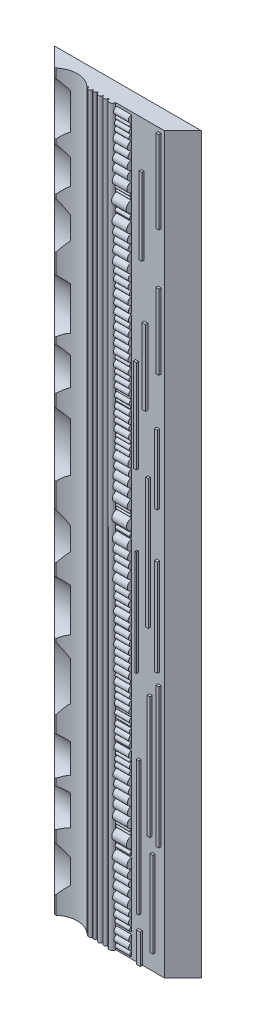
SolidWorks part; units mm, degrees
ref_plane "前视基准面" through (0, 0, 0) normal (0, 0, 1) x (1, 0, 0)
ref_plane "上视基准面" through (0, 0, 0) normal (0, 1, 0) x (1, 0, 0)
ref_plane "右视基准面" through (0, 0, 0) normal (1, 0, 0) x (0, 0, -1)
sketch "草图1" plane through (0, 0, 0) normal (0, 0, 1) x (1, 0, 0)
  line L1 (0, 0) -> (50, 0)
  line L2 (0, 0) -> (0, 10)
  line L3 (0, 10) -> (50, 10)
  line L4 (50, 0) -> (50, 10)
sketch "草图2" plane through (0, 0, 0) normal (1, 0, 0) x (0, 0, -1)
  line L0 (0, 10) -> (-1.257, 8.743)
  line L2 (0, 0) -> (0, 10)
  line L4 (-1.257, 1.257) -> (-1.257, 8.743)
  line L5 (0, 0) -> (-1.257, 1.257)
extrude "凸台-拉伸1" add sketch "草图2" along normal blind 50
sketch "草图4" plane through (0, 0, 0) normal (0, 1, 0) x (1, 0, 0)
  line L0 (0.6235, -1.257) -> (4.1918, -1.257)
  line L1 (45.7548, -1.257) -> (48.7813, -1.257)
  line L2 (42.3754, -1.257) -> (44.9543, -1.257)
  line L3 (39.288, -1.257) -> (41.9161, -1.257)
  line L4 (33.8809, -1.257) -> (38.1709, -1.257)
  line L5 (30.0238, -1.257) -> (33.6686, -1.257)
  line L6 (20.0613, -1.257) -> (24.3897, -1.257)
  line L7 (12.228, -1.257) -> (15.8643, -1.257)
  line L8 (7.7148, -1.257) -> (10.8649, -1.257)
  line L9 (4.5051, -1.257) -> (7.4446, -1.257)
  line L10 (16.3112, -1.257) -> (19.2037, -1.257)
  line L11 (26.0537, -1.257) -> (29.207, -1.257)
  arc A0 (4.1918, -1.257) -> (0.6235, -1.257) centre (2.4077, -3.4751) ccw
  arc A1 (7.4446, -1.257) -> (4.5051, -1.257) centre (5.9749, -3.1147) ccw
  arc A4 (15.8643, -1.257) -> (12.228, -1.257) centre (14.0461, -2.7544) ccw
  arc A6 (24.3897, -1.257) -> (20.0613, -1.257) centre (22.2255, -3.7994) ccw
  arc A10 (41.9161, -1.257) -> (39.288, -1.257) centre (40.6021, -2.1419) ccw
  arc A11 (44.9543, -1.257) -> (42.3754, -1.257) centre (43.6648, -1.9257) ccw
  arc A12 (48.7813, -1.257) -> (45.7548, -1.257) centre (47.2681, -3.3782) ccw
  arc A13 (10.8649, -1.257) -> (7.7148, -1.257) centre (9.2898, -3.7994) ccw
  arc A14 (19.2037, -1.257) -> (16.3112, -1.257) centre (17.7575, -2.7544) ccw
  arc A15 (29.207, -1.257) -> (26.0537, -1.257) centre (27.6304, -3.7994) ccw
  arc A16 (33.6686, -1.257) -> (30.0238, -1.257) centre (31.8462, -2.7544) ccw
  arc A17 (38.1709, -1.257) -> (33.8809, -1.257) centre (36.0259, -5.1131) ccw
extrude "切除-拉伸1" cut sketch "草图4" along normal blind 2
sketch "草图5" plane through (0, 0, 0) normal (-1, 0, 0) x (0, 0, 1)
  circle A0 centre (2.4471, 2.398) radius 1.5913
extrude "切除-拉伸2" cut sketch "草图5" against normal blind 50
sketch "草图6" plane through (0, 0, 0) normal (-1, 0, 0) x (0, 0, 1)
  line L0 (1.257, 8.743) -> (1.257, 3.4545) construction
  circle A0 centre (1.257, 3.7317) radius 0.155
  circle A1 centre (1.257, 4.0208) radius 0.1212
  circle A2 centre (1.257, 4.4031) radius 0.1679
  circle A3 centre (1.257, 4.7668) radius 0.1585
  circle A4 centre (1.257, 5.2052) radius 0.2145
extrude "凸台-拉伸2" add sketch "草图6" against normal blind 50
ref_plane "基准面1" through (0, 5.5, 0) normal (0, 1, 0) x (1, 0, 0)
sketch "草图7" plane through (0, 5.5, 0) normal (0, 1, 0) x (1, 0, 0)
  line L0 (0, -1.257) -> (50, -1.257) construction
  line L1 (50, -1.257) -> (0, -1.257) construction
  line L2 (50, -1.257) -> (0, -1.257) construction
  line L3 (0, -1.257) -> (50, -1.257) construction
  circle A0 centre (0.4046, -1.257) radius 0.2266
  circle A2 centre (1.4918, -1.257) radius 0.1784
  circle A3 centre (1.9842, -1.257) radius 0.2787
  circle A5 centre (3.1418, -1.257) radius 0.2991
  circle A6 centre (3.7531, -1.257) radius 0.2977
  circle A7 centre (4.4332, -1.257) radius 0.3186
  circle A9 centre (5.5815, -1.257) radius 0.3658
  circle A11 centre (6.8227, -1.257) radius 0.3345
  circle A12 centre (7.4693, -1.257) radius 0.2913
  circle A13 centre (8.0156, -1.257) radius 0.2335
  circle A14 centre (8.56, -1.257) radius 0.2885
  circle A15 centre (9.2122, -1.257) radius 0.3087
  circle A16 centre (9.7882, -1.257) radius 0.2281
  circle A17 centre (10.275, -1.257) radius 0.2342
  circle A19 centre (11.1651, -1.257) radius 0.2558
  circle A20 centre (11.6798, -1.257) radius 0.2208
  circle A21 centre (12.2242, -1.257) radius 0.2248
  circle A22 centre (12.6515, -1.257) radius 0.1789
  circle A23 centre (13.0956, -1.257) radius 0.2431
  circle A24 centre (13.5769, -1.257) radius 0.2235
  circle A25 centre (14.06, -1.257) radius 0.2323
  circle A26 centre (14.5449, -1.257) radius 0.2426
  circle A27 centre (14.9389, -1.257) radius 0.1416
  circle A28 centre (15.3291, -1.257) radius 0.2354
  circle A29 centre (15.7639, -1.257) radius 0.1707
  circle A30 centre (16.1708, -1.257) radius 0.193
  circle A33 centre (17.1713, -1.257) radius 0.1734
  circle A35 centre (17.8158, -1.2454) radius 0.1867
  circle A36 centre (18.2231, -1.257) radius 0.215
  circle A37 centre (18.6402, -1.257) radius 0.1872
  circle A38 centre (0.798, -1.257) radius 0.1224
  circle A39 centre (1.1234, -1.257) radius 0.1732
  circle A40 centre (2.5672, -1.257) radius 0.2444
  circle A41 centre (4.8855, -1.257) radius 0.1209
  circle A42 centre (5.1143, -1.257) radius 0.0868
  circle A43 centre (6.0345, -1.257) radius 0.0609
  circle A44 centre (6.248, -1.257) radius 0.1326
  circle A45 centre (10.7118, -1.257) radius 0.155
  circle A46 centre (16.6041, -1.257) radius 0.198
  circle A47 centre (16.9041, -1.257) radius 0.0631
  circle A48 centre (17.4633, -1.257) radius 0.0861
  circle A49 centre (19.1512, -1.2381) radius 0.2266
  circle A50 centre (20.2383, -1.2381) radius 0.1784
  circle A51 centre (20.7307, -1.2381) radius 0.2787
  circle A52 centre (21.8883, -1.2381) radius 0.2991
  circle A53 centre (22.4996, -1.2381) radius 0.2977
  circle A54 centre (23.1797, -1.2381) radius 0.3186
  circle A55 centre (24.328, -1.2381) radius 0.3658
  circle A56 centre (25.5692, -1.2381) radius 0.3345
  circle A57 centre (26.2158, -1.2381) radius 0.2913
  circle A58 centre (26.7621, -1.2381) radius 0.2335
  circle A59 centre (27.3065, -1.2381) radius 0.2885
  circle A60 centre (27.9587, -1.2381) radius 0.3087
  circle A61 centre (28.5347, -1.2381) radius 0.2281
  circle A62 centre (29.0216, -1.2381) radius 0.2342
  circle A63 centre (29.9116, -1.2381) radius 0.2558
  circle A64 centre (30.4263, -1.2381) radius 0.2208
  circle A65 centre (30.9707, -1.2381) radius 0.2248
  circle A66 centre (31.3981, -1.2381) radius 0.1789
  circle A67 centre (31.8422, -1.2381) radius 0.2431
  circle A68 centre (32.3234, -1.2381) radius 0.2235
  circle A69 centre (32.8065, -1.2381) radius 0.2323
  circle A70 centre (33.2915, -1.2381) radius 0.2426
  circle A71 centre (33.6854, -1.2381) radius 0.1416
  circle A72 centre (34.0756, -1.2381) radius 0.2354
  circle A73 centre (34.5104, -1.2381) radius 0.1707
  circle A74 centre (34.9173, -1.2381) radius 0.193
  circle A75 centre (35.9179, -1.2381) radius 0.1734
  circle A76 centre (36.5624, -1.2265) radius 0.1867
  circle A77 centre (36.9696, -1.2381) radius 0.215
  circle A78 centre (37.3868, -1.2381) radius 0.1872
  circle A79 centre (19.5445, -1.2381) radius 0.1224
  circle A80 centre (19.8699, -1.2381) radius 0.1732
  circle A81 centre (21.3138, -1.2381) radius 0.2444
  circle A82 centre (23.6321, -1.2381) radius 0.1209
  circle A83 centre (23.8608, -1.2381) radius 0.0868
  circle A84 centre (24.7811, -1.2381) radius 0.0609
  circle A85 centre (24.9946, -1.2381) radius 0.1326
  circle A86 centre (29.4583, -1.2381) radius 0.155
  circle A87 centre (35.3507, -1.2381) radius 0.198
  circle A88 centre (35.6506, -1.2381) radius 0.0631
  circle A89 centre (36.2099, -1.2381) radius 0.0861
  circle A90 centre (37.9239, -1.2415) radius 0.2266
  circle A91 centre (39.0111, -1.2415) radius 0.1784
  circle A92 centre (39.5035, -1.2415) radius 0.2787
  circle A93 centre (40.6611, -1.2415) radius 0.2991
  circle A94 centre (41.2724, -1.2415) radius 0.2977
  circle A95 centre (41.9525, -1.2415) radius 0.3186
  circle A96 centre (43.1008, -1.2415) radius 0.3658
  circle A97 centre (44.342, -1.2415) radius 0.3345
  circle A98 centre (44.9886, -1.2415) radius 0.2913
  circle A99 centre (45.5349, -1.2415) radius 0.2335
  circle A100 centre (46.0793, -1.2415) radius 0.2885
  circle A101 centre (46.7315, -1.2415) radius 0.3087
  circle A102 centre (47.3075, -1.2415) radius 0.2281
  circle A103 centre (47.7943, -1.2415) radius 0.2342
  circle A120 centre (38.3173, -1.2415) radius 0.1224
  circle A121 centre (38.6427, -1.2415) radius 0.1732
  circle A122 centre (40.0865, -1.2415) radius 0.2444
  circle A123 centre (42.4048, -1.2415) radius 0.1209
  circle A124 centre (42.6336, -1.2415) radius 0.0868
  circle A125 centre (43.5538, -1.2415) radius 0.0609
  circle A126 centre (43.7674, -1.2415) radius 0.1326
  circle A127 centre (48.2311, -1.2415) radius 0.155
  circle A131 centre (48.7791, -1.224) radius 0.2281
  circle A132 centre (49.2659, -1.224) radius 0.2342
  circle A133 centre (49.7027, -1.224) radius 0.155
extrude "凸台-拉伸3" add sketch "草图7" along normal blind 1
sketch "草图8" plane through (0, 0, 1.257) normal (0, 0, 1) x (1, 0, 0)
  line L0 (50, 0) -> (50, 10) construction
  line L1 (0.2752, 8.5145) -> (5.8992, 8.5145)
  line L2 (0.2752, 8.5145) -> (0.2752, 8.3071)
  line L3 (0.2752, 8.3071) -> (5.8992, 8.3071)
  line L4 (5.8992, 8.5145) -> (5.8992, 8.3071)
  line L5 (3.0872, 7.3482) -> (8.3354, 7.3482)
  line L6 (3.0872, 7.3482) -> (3.0872, 7.1538)
  line L7 (3.0872, 7.1538) -> (8.3354, 7.1538)
  line L8 (8.3354, 7.3482) -> (8.3354, 7.1538)
  line L9 (9.385, 8.5145) -> (14.4777, 8.5145)
  line L10 (9.385, 8.5145) -> (9.385, 8.3071)
  line L11 (9.385, 8.3071) -> (14.4777, 8.3071)
  line L12 (14.4777, 8.5145) -> (14.4777, 8.3071)
  line L13 (11.9313, 7.6074) -> (17.0564, 7.6074)
  line L14 (11.9313, 7.6074) -> (11.9313, 7.3482)
  line L15 (11.9313, 7.3482) -> (17.0564, 7.3482)
  line L16 (17.0564, 7.6074) -> (17.0564, 7.3482)
  line L17 (14.4939, 6.9724) -> (20.8274, 6.9724)
  line L18 (14.4939, 6.9724) -> (14.4939, 6.7651)
  line L19 (14.4939, 6.7651) -> (20.8274, 6.7651)
  line L20 (20.8274, 6.9724) -> (20.8274, 6.7651)
  line L21 (17.7692, 8.4108) -> (22.4731, 8.4108)
  line L22 (17.7692, 8.4108) -> (17.7692, 8.2034)
  line L23 (17.7692, 8.2034) -> (22.4731, 8.2034)
  line L24 (22.4731, 8.4108) -> (22.4731, 8.2034)
  line L25 (20.931, 7.6074) -> (29.7817, 7.6074)
  line L26 (20.931, 7.6074) -> (20.931, 7.7888)
  line L27 (20.931, 7.7888) -> (29.7817, 7.7888)
  line L28 (29.7817, 7.6074) -> (29.7817, 7.7888)
  line L29 (25.5443, 8.4108) -> (32.1142, 8.4108)
  line L30 (25.5443, 8.4108) -> (25.5443, 8.2034)
  line L31 (25.5443, 8.2034) -> (32.1142, 8.2034)
  line L32 (32.1142, 8.4108) -> (32.1142, 8.2034)
  line L33 (25.6868, 6.9724) -> (32.8529, 6.9724)
  line L34 (25.6868, 6.9724) -> (25.6868, 6.8687)
  line L35 (25.6868, 6.8687) -> (32.8529, 6.8687)
  line L36 (32.8529, 6.9724) -> (32.8529, 6.8687)
  line L37 (33.747, 7.6981) -> (42.0664, 7.6981)
  line L38 (33.747, 7.6981) -> (33.747, 7.9054)
  line L39 (33.747, 7.9054) -> (42.0664, 7.9054)
  line L40 (42.0664, 7.6981) -> (42.0664, 7.9054)
  line L41 (32.8529, 8.5145) -> (42.3774, 8.5145)
  line L42 (32.8529, 8.5145) -> (32.8529, 8.3071)
  line L43 (32.8529, 8.3071) -> (42.3774, 8.3071)
  line L44 (42.3774, 8.5145) -> (42.3774, 8.3071)
  line L45 (37.9067, 7.1538) -> (47.0036, 7.1538)
  line L46 (37.9067, 7.1538) -> (37.9067, 6.9724)
  line L47 (37.9067, 6.9724) -> (47.0036, 6.9724)
  line L48 (47.0036, 7.1538) -> (47.0036, 6.9724)
  line L49 (42.9994, 8.1127) -> (48.8307, 8.1127)
  line L50 (42.9994, 8.1127) -> (42.9994, 7.9054)
  line L51 (42.9994, 7.9054) -> (48.8307, 7.9054)
  line L52 (48.8307, 8.1127) -> (48.8307, 7.9054)
  line L53 (47.9625, 7.251) -> (50, 7.251)
  line L54 (47.9625, 7.251) -> (47.9625, 6.9724)
  line L55 (47.9625, 6.9724) -> (50, 6.9724)
  line L56 (50, 7.251) -> (50, 6.9724)
extrude "凸台-拉伸4" add sketch "草图8" along normal blind 0.15
move or copy body "实体-移动/复制1" bodies to move or copy 112 copy no rotation origin (25, 5, 0) rotation axis (0, 0, -1) rotation angle 90
move or copy body "实体-移动/复制2" bodies to move or copy 113 copy no translate (-20, 20, 0)
